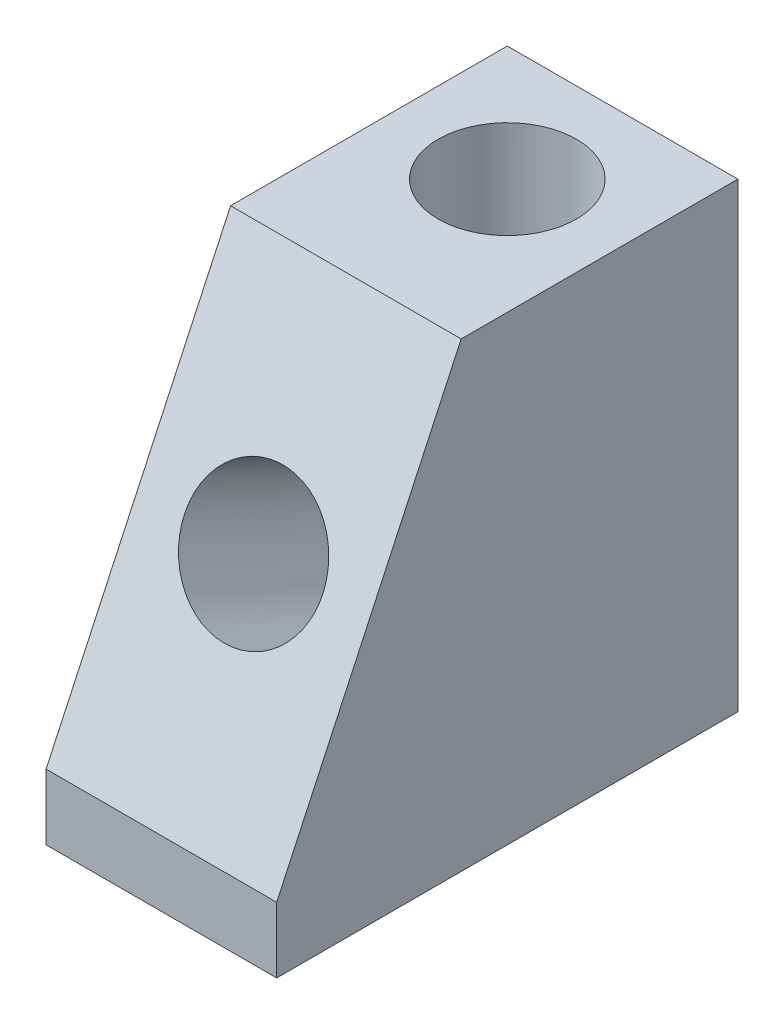
SolidWorks part; units mm, degrees
ref_plane "前视基准面" through (0, 0, 0) normal (0, 0, 1) x (1, 0, 0)
ref_plane "上视基准面" through (0, 0, 0) normal (0, 1, 0) x (1, 0, 0)
ref_plane "右视基准面" through (0, 0, 0) normal (1, 0, 0) x (0, 0, -1)
other "Configuration Table"
sketch "草图1" plane through (0, 0, 0) normal (0, 1, 0) x (1, 0, 0)
  line L1 (0, 0) -> (5, 0)
  line L2 (0, 0) -> (0, 10)
  line L3 (0, 10) -> (5, 10)
  line L4 (5, 0) -> (5, 10)
  circle A0 centre (2.5, 7.5) radius 1.5
  dimension "D3" = 3
  dimension "D1" = 5
  dimension "D2" = 10
  dimension "D4" = 7.5
  dimension "D5" = 2.5
extrude "凸台-拉伸1" add sketch "草图1" along normal blind 10
sketch "草图2" plane through (5, 0, 0) normal (1, 0, 0) x (0, 0, -1)
  line L0 (0, 1.422) -> (4, 10)
  line L1 (0, 10) -> (0, 0) construction
  line L2 (0, 10) -> (10, 10) construction
  line L3 (0, 1.422) -> (0, 10)
  line L4 (0, 10) -> (4, 10)
  dimension "D1" = 65
  dimension "D2" = 4
extrude "切除-拉伸1" cut sketch "草图2" against normal blind 5
sketch "草图3" plane through (0, 0.254, 0.5446) normal (0, 0.4226, 0.9063) x (1, 0, 0)
  line L0 (5, 1.2887) -> (0, 10.7536) construction
  line L1 (0, 10.7536) -> (0, 1.2887)
  line L2 (0, 1.2887) -> (5, 10.7536) construction
  circle A0 centre (2.5, 6.0211) radius 1.5
  dimension "D1" = 3
extrude "切除-拉伸2" cut sketch "草图3" against normal through all contours A0
